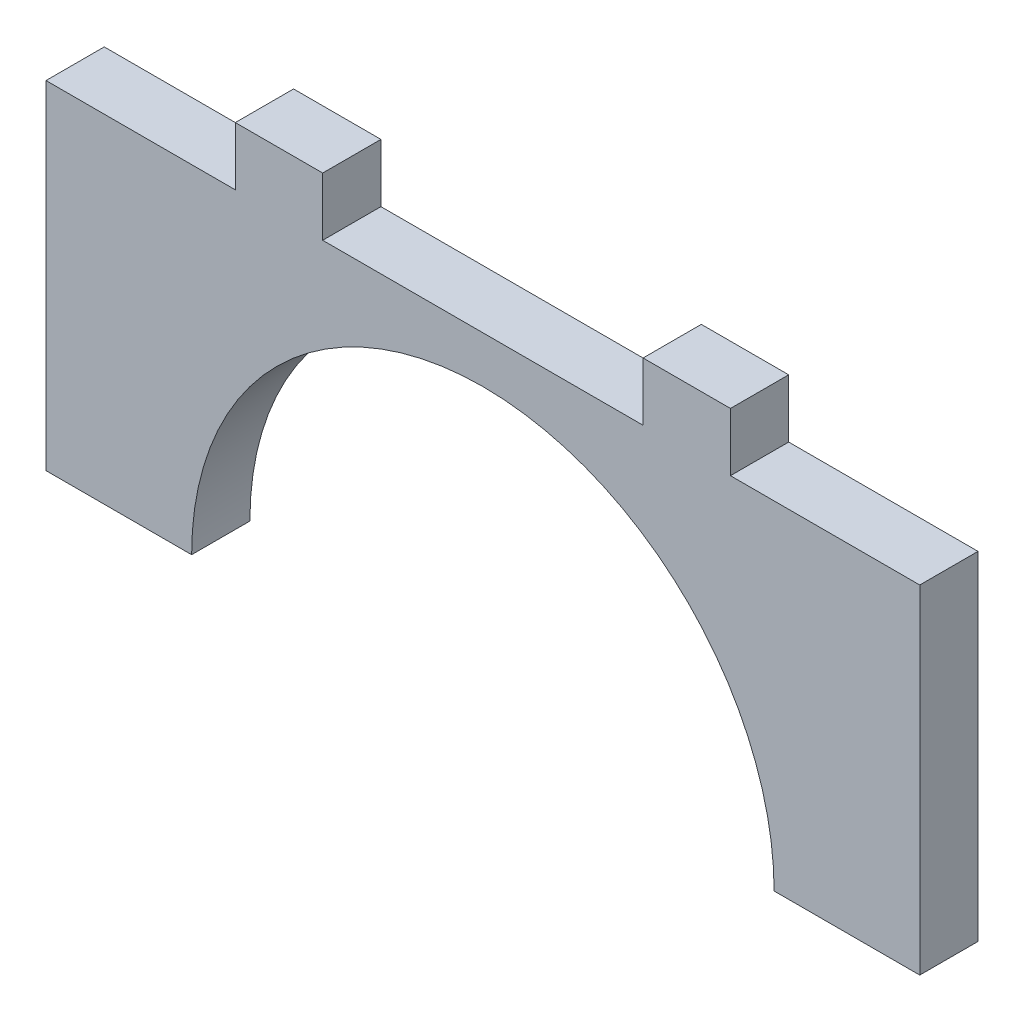
SolidWorks part; units mm, degrees
material "Acrylic (Medium-high impact)"
ref_plane "Front Plane" through (0, 0, 0) normal (0, 0, 1) x (1, 0, 0)
ref_plane "Top Plane" through (0, 0, 0) normal (0, 1, 0) x (1, 0, 0)
ref_plane "Right Plane" through (0, 0, 0) normal (1, 0, 0) x (0, 0, -1)
sketch "Sketch1" plane through (0, 0, 0) normal (0, 0, 1) x (1, 0, 0)
  line L0 (-34.925, 215.9) -> (-34.925, 228.6) construction
  line L1 (95.25, 142.24) -> (63.5, 142.24)
  line L2 (95.25, 142.24) -> (95.25, 215.9)
  line L3 (95.25, 215.9) -> (53.975, 215.9)
  line L4 (-95.25, 142.24) -> (-95.25, 215.9)
  line L5 (-53.975, 215.9) -> (-53.975, 228.6) construction
  line L6 (-63.5, 142.24) -> (-95.25, 142.24)
  line L7 (-53.975, 228.6) -> (-34.925, 228.6) construction
  line L8 (34.925, 215.9) -> (34.925, 228.6) construction
  line L9 (34.925, 228.6) -> (53.975, 228.6) construction
  line L10 (53.975, 215.9) -> (53.975, 228.6) construction
  line L11 (-34.925, 215.9) -> (-34.925, 228.6)
  line L12 (-53.975, 215.9) -> (-53.975, 228.6)
  line L13 (-53.975, 228.6) -> (-34.925, 228.6)
  line L14 (34.925, 215.9) -> (34.925, 228.6)
  line L15 (34.925, 228.6) -> (53.975, 228.6)
  line L16 (53.975, 215.9) -> (53.975, 228.6)
  line L17 (34.925, 215.9) -> (-34.925, 215.9)
  line L18 (-53.975, 215.9) -> (-95.25, 215.9)
  arc A0 (63.5, 142.24) -> (-63.5, 142.24) centre (0, 142.24) ccw
  arc A1 (0, 78.74) -> (63.5, 142.24) centre (0, 142.24) ccw construction
extrude "Extrude1" add sketch "Sketch1" against normal blind 12.7 contours A0 L1 L2 L3 L4 L6
